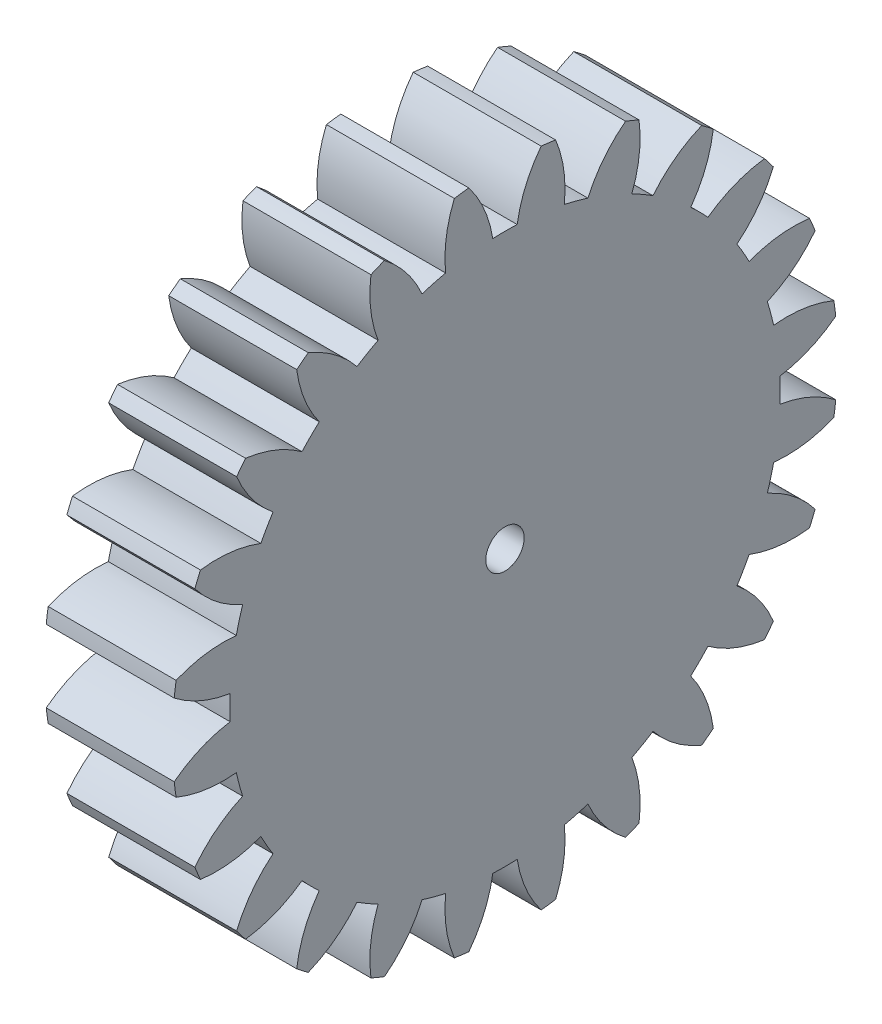
SolidWorks part; units mm, degrees
material "20% Eyballed PLA"
ref_plane "Plane1" through (0, 0, 0) normal (0, 0, 1) x (1, 0, 0)
ref_plane "Plane2" through (0, 0, 0) normal (0, 1, 0) x (1, 0, 0)
ref_plane "Plane3" through (0, 0, 0) normal (1, 0, 0) x (0, 0, -1)
sketch "HoldingSke" plane through (0, 0, 0) normal (0, 1, 0) x (1, 0, 0)
  line L0 (0, 0) -> (0.4568, -0.2034)
  line L1 (-15, 0) -> (100, 0) construction
  line L2 (0, 0) -> (-2.1039, 2.3779)
  line L3 (0, 0) -> (-11.863, 4.5341)
  line L4 (0, 0) -> (7.8894, 3.5126)
  line L5 (0, 0) -> (-46.8476, -17.4728)
  line L6 (0, 0) -> (-8.2896, -5.593)
  line L7 (-2.1039, 2.3779) -> (8.6586, 51.2059)
  line L8 (-76.2, 54.61) -> (-75.7, 54.61)
  line L9 (-71.009, 38.7566) -> (-53.1078, 45.2721)
  line L10 (-76.2, 71.12) -> (104.1128, 71.12)
  line L11 (0, 0) -> (-10, 0)
  line L12 (-76.2, 101.6) -> (-76.133, 101.6)
  line L13 (24.9733, 27.94) -> (52.9518, 28.4284)
  line L14 (24.9733, 27.94) -> (24.9743, 27.94)
  line L15 (24.9733, 27.94) -> (100.4006, 29.5858)
  line L16 (-63.627, -2) -> (-12.827, -2)
  circle A0 centre (0, 0) radius 1.5
  circle A1 centre (0, 0) radius 21.499
  circle A2 centre (0, 0) radius 37.5
  circle A3 centre (0, 0) radius 1.5
  dimension "MHD" = 42.998
  dimension "Hub_dia" = 75
  dimension "Bore" = 3
  dimension "MBD" = 3
  dimension "Num_teeth" = 24
  dimension "Pitch" = 0.5
  dimension "Overall_len" = 50
  dimension "Show_teeth" = 24
  dimension "Thickness" = 10
  dimension "OAL" = 50.0001
  dimension "T_dim" = 0.5
  dimension "Ap" = 20
  dimension "H" = 19.05
  dimension "Pitch_radius" = 180.3128
  dimension "Width" = 10
  dimension "Backlash" = 0.067
  dimension "Addendum_fac" = 1
  dimension "Dedendum_fac" = 1.25
  dimension "Clearance_fac" = 0.25
  dimension "Dedendum_add" = 0.001
  dimension "Module" = 2
sketch "BasProSke" plane through (0, 0, 0) normal (0, 1, 0) x (1, 0, 0)
  line L0 (-10, 0) -> (60, 0) construction
  line L1 (0, 0) -> (0, 26)
  line L2 (0, 0) -> (10, 0)
  line L3 (10, 0) -> (10, 26)
  line L4 (10, 26) -> (0, 26)
  dimension "Thickness" = 10
  dimension "Diameter" = 52
revolve "Base-Revolve" add sketch "BasProSke" angle 360 about L0
sketch "TooCutSke" plane through (0, 0, 0) normal (1, 0, 0) x (0, 0, -1)
  line L1 (0, 0) -> (0, 107) construction
  line L2 (0, 0) -> (-1.6869, 23.9406) construction
  line L3 (0, 0) -> (-6.2538, 47.5021) construction
  line L4 (-1.6869, 23.9406) -> (-3.1269, 23.7511) construction
  arc A0 (0.9529, 21.4779) -> (-0.9529, 21.4779) centre (0, 0) ccw
  arc A1 (2.8465, 25.8693) -> (-2.8465, 25.8693) centre (0, 0) ccw
  circle A2 centre (0, 0) radius 24 construction
  circle A3 centre (0, 0) radius 22.5526 construction
  arc A4 (-0.9529, 21.4779) -> (-2.8465, 25.8693) centre (-10.4373, 19.9921) ccw
  arc A5 (2.8465, 25.8693) -> (0.9529, 21.4779) centre (10.4373, 19.9921) ccw
  dimension "Root_dia" = 42.998
  dimension "Overcut_dia" = 52.0508
  dimension "Pitch_dia" = 48
  dimension "Base_dia" = 45.1052
  dimension "Flank_rad" = 9.6
  dimension "Half_ang" = 7.5
  dimension "Half_CT" = 1.4524
extrude "ToothCut" cut sketch "TooCutSke" along normal through all
fillet "Breaks" [suppressed] radius 0.04
fillet "RootFillets" [suppressed] radius 0.501
pattern_circular "TeethCuts" count 24 every 15 about axis through (-10, 0, 0) along (1, 0, 0) of "ToothCut", "RootFillets", "Breaks"
sketch "HubNeaOneSke" plane through (0, 0, 0) normal (-1, 0, 0) x (0, 0, 1)
  circle A0 centre (0, 0) radius 21.499
  dimension "Diameter" = 42.998
extrude "HubNearOne" [suppressed] add sketch "HubNeaOneSke" along normal blind 40.0001
sketch "HubNeaBotSke" plane through (0, 0, 0) normal (-1, 0, 0) x (0, 0, 1)
  circle A0 centre (0, 0) radius 21.499
  dimension "Diameter" = 42.998
extrude "HubNearBoth" [suppressed] add sketch "HubNeaBotSke" along normal blind 20
ref_plane "FarPln" through (10, 0, 0) normal (1, 0, 0) x (0, 0, -1)
sketch "HubFarSke" plane through (10, 0, 0) normal (1, 0, 0) x (0, 0, -1)
  circle A0 centre (0, 0) radius 21.499
  dimension "Diameter" = 42.998
extrude "HubFar" [suppressed] add sketch "HubFarSke" along normal blind 20
sketch "BorSke" plane through (0, 0, 0) normal (1, 0, 0) x (0, 0, -1)
  circle A0 centre (0, 0) radius 1.5
  dimension "Diameter" = 3
extrude "Bore" cut sketch "BorSke" along normal mid plane 100.0001
sketch "KeySke" plane through (0, 0, 0) normal (1, 0, 0) x (0, 0, -1)
  line L0 (-0.6, 0) -> (-0.6, 2)
  line L1 (-0.6, 2) -> (0.6, 2)
  line L2 (0.6, 2) -> (0.6, 0)
  line L3 (0, 0) -> (0, 34) construction
  line L4 (-0.6, 0) -> (0.6, 0)
  dimension "Offset" = 2
  dimension "Width" = 1.2
extrude "Keyway" [suppressed] cut sketch "KeySke" along normal mid plane 100.0001
pattern_circular "Keyway2" [suppressed] count 2 every 90 about axis through (-10, 0, 0) along (1, 0, 0)
equation "' \"Module@HoldingSke\" = 6.35"
equation "' \"Num_teeth@HoldingSke\" = 12"
equation "' \"Ap@HoldingSke\" =  20"
equation "' \"Ap@HoldingSke\" = 20"
equation "' \"Width@HoldingSke\" = 0.5 * 25.4"
equation "' \"Hub_dia@HoldingSke\"= 1 * 25.4"
equation "' \"Hub_dia@HoldingSke\" = 1 * 25.4"
equation "' \"Overall_len@HoldingSke\" = 1.0 * 25.4"
equation "' \"Bore@HoldingSke\" = 0.75 * 25.4"
equation "' \"T_dim@HoldingSke\" = 0.1 * 25.4"
equation "' \"Width@KeySke\" = 0.25 * 25.4"
equation "' \"Show_teeth@HoldingSke\" = 13"
equation "' \"Backlash@HoldingSke\" = 0.009 * 25.4"
equation "' \"Addendum_fac@HoldingSke\" = 1.0"
equation "' \"Dedendum_fac@HoldingSke\" = 1.25"
equation "' \"Dedendum_add@HoldingSke\" = 0.00005 * 25.4"
equation "' \"Clearance_fac@HoldingSke\" = 0.25"
equation "\"Pitch@HoldingSke\" = 1 / \"Module@HoldingSke\""
equation "\"Overcut_dia@TooCutSke\" = (\"Num_teeth@HoldingSke\" + 2 * \"Addendum_fac@HoldingSke\") / \"Pitch@HoldingSke\" + 0.002 * 25.4"
equation "\"Pitch_dia@TooCutSke\" = \"Num_teeth@HoldingSke\" / \"Pitch@HoldingSke\""
equation "\"Base_dia@TooCutSke\" = \"Num_teeth@HoldingSke\" / \"Pitch@HoldingSke\" * cos((\"Ap@HoldingSke\"  * 3.14159265 / 180))"
equation "\"Root_dia@TooCutSke\" = (\"Num_teeth@HoldingSke\" + 2) / \"Pitch@HoldingSke\" - 2 * (\"Addendum_fac@HoldingSke\" + \"Dedendum_fac@HoldingSke\") / \"Pitch@HoldingSke\" - \"Dedendum_add@HoldingSke\" * 2"
equation "\"Half_ang@TooCutSke\" = 180 / \"Num_teeth@HoldingSke\""
equation "\"Half_CT@TooCutSke\" = \"Num_teeth@HoldingSke\" / \"Pitch@HoldingSke\" * sin((3.14159265 / 2 / \"Num_teeth@HoldingSke\")) / 2 - 7 * \"Backlash@HoldingSke\" / 4"
equation "\"Flank_rad@TooCutSke\" = \"Num_teeth@HoldingSke\" / \"Pitch@HoldingSke\" / 5"
equation "\"Radius@RootFillets\" = \"Clearance_fac@HoldingSke\" / \"Pitch@HoldingSke\" + \"Dedendum_add@HoldingSke\""
equation "\"Break_rad@Breaks\" = 0.02 / \"Pitch@HoldingSke\""
equation "\"Thickness@HoldingSke\" = \"Width@HoldingSke\""
equation "\"OAL@HoldingSke\" = \"Thickness@HoldingSke\""
equation "\"MHD@HoldingSke\" = (\"Num_teeth@HoldingSke\" + 2) / \"Pitch@HoldingSke\" - 2 * (\"Addendum_fac@HoldingSke\" + \"Dedendum_fac@HoldingSke\")  / \"Pitch@HoldingSke\" - \"Dedendum_add@HoldingSke\" * 2"
equation "\"MBD@HoldingSke\" = (\"Num_teeth@HoldingSke\" + 2) / \"Pitch@HoldingSke\" - 2 * (\"Addendum_fac@HoldingSke\" + \"Dedendum_fac@HoldingSke\")  / \"Pitch@HoldingSke\" - \"Dedendum_add@HoldingSke\" * 2 - 0.002 * 25.4"
equation "\"MHD@HoldingSke\" = ((sgn( \"MHD@HoldingSke\" - \"Hub_dia@HoldingSke\" )-1)*( \"MHD@HoldingSke\" - \"Hub_dia@HoldingSke\" ))/-2+ \"Hub_dia@HoldingSke\""
equation "\"MBD@HoldingSke\" = ((sgn( \"MBD@HoldingSke\" - \"Bore@HoldingSke\" )-1)*( \"MBD@HoldingSke\" - \"Bore@HoldingSke\" ))/-2+ \"Bore@HoldingSke\""
equation "\"OAL@HoldingSke\" = ((sgn( \"OAL@HoldingSke\" - \"Overall_len@HoldingSke\" )+1)*( \"OAL@HoldingSke\" - \"Overall_len@HoldingSke\" ))/2 + \"Overall_len@HoldingSke\" + 0.000002 * 25.4"
equation "\"Num_teeth@TeethCuts\" = int( \"Show_teeth@HoldingSke\" ) + 1"
equation "\"Num_teeth@TeethCuts\" = ((sgn( \"Num_teeth@TeethCuts\" - \"Num_teeth@HoldingSke\" )-1)*( \"Num_teeth@TeethCuts\" - \"Num_teeth@HoldingSke\" ))/-2+ \"Num_teeth@HoldingSke\""
equation "\"Num_teeth@TeethCuts\" = ((sgn( \"Num_teeth@TeethCuts\" - 2.0)+1)*( \"Num_teeth@TeethCuts\" - 2.0))/2 +2.0"
equation "\"Angle@TeethCuts\" = 360.0 / \"Num_teeth@HoldingSke\""
equation "\"Diameter@BasProSke\" = (\"Num_teeth@HoldingSke\" + 2 * \"Addendum_fac@HoldingSke\") / \"Pitch@HoldingSke\""
equation "\"Thickness@BasProSke\"  = \"Thickness@HoldingSke\""
equation "' \"Fillet_rad@BasProSke\" =  \"Thickness@HoldingSke\" * 0.05"
equation "' \"Fillet_rad@BasProSke\" = \"Thickness@HoldingSke\" * 0.05"
equation "\"MHD@HoldingSke\" = ((sgn( \"MHD@HoldingSke\" - \"Root_dia@TooCutSke\" )-1)*( \"MHD@HoldingSke\" - \"Root_dia@TooCutSke\" ))/-2+ \"Root_dia@TooCutSke\""
equation "\"Diameter@HubNeaOneSke\" = \"MHD@HoldingSke\""
equation "\"Length@HubNearOne\" = \"OAL@HoldingSke\" - \"Thickness@BasProSke\""
equation "\"Diameter@HubNeaBotSke\" = \"MHD@HoldingSke\""
equation "\"Length@HubNearBoth\" = ( \"OAL@HoldingSke\" - \"Thickness@BasProSke\" ) / 2.0"
equation "\"Thickness@FarPln\" = \"Thickness@BasProSke\""
equation "\"Diameter@HubFarSke\" = \"MHD@HoldingSke\""
equation "\"Length@HubFar\" = ( \"OAL@HoldingSke\" - \"Thickness@BasProSke\" ) / 2.0"
equation "\"Diameter@BorSke\" = \"MBD@HoldingSke\""
equation "\"D1@Bore\" = \"OAL@HoldingSke\" * 2.0"
equation "\"D1@Keyway\" = \"OAL@HoldingSke\" * 2.0"
equation "\"Offset@KeySke\" = \"T_dim@HoldingSke\" + \"MBD@HoldingSke\" / 2.0"
